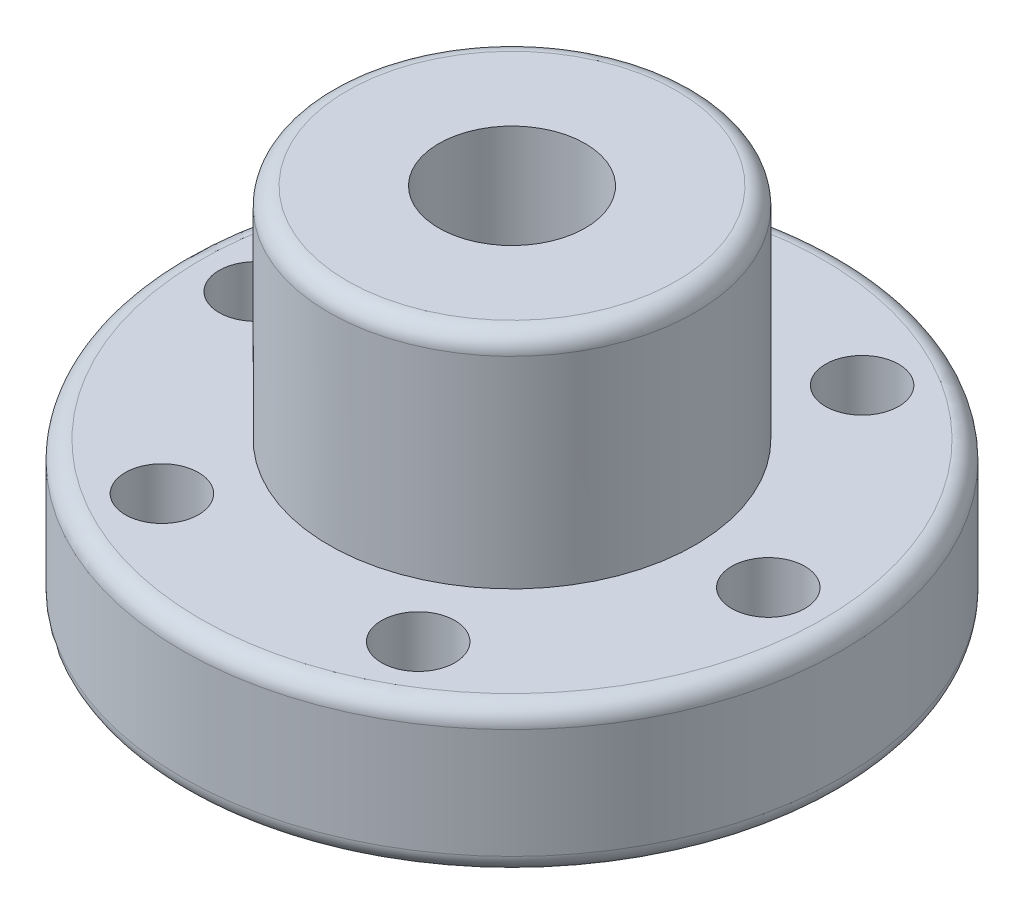
SolidWorks part; units mm, degrees
ref_plane "Front Plane" through (0, 0, 0) normal (0, 0, 1) x (1, 0, 0)
ref_plane "Top Plane" through (0, 0, 0) normal (0, 1, 0) x (1, 0, 0)
ref_plane "Right Plane" through (0, 0, 0) normal (1, 0, 0) x (0, 0, -1)
sketch "Sketch1" plane through (0, 0, 0) normal (0, 0, 1) x (1, 0, 0)
  line L0 (0, 0) -> (0, 20)
  line L1 (0, 20) -> (6, 20)
  line L2 (6, 20) -> (6, 8)
  line L3 (6, 8) -> (14, 8)
  line L4 (14, 8) -> (14, 0)
  line L5 (14, 0) -> (0, 0)
  line L6 (-4, 0) -> (-4, 5.745) construction
  dimension "D1" = 4
  dimension "D2" = 10
  dimension "D3" = 12
  dimension "D4" = 8
  dimension "D5" = 18
revolve "Revolve1" add sketch "Sketch1" angle 360 about L6
fillet "Fillet1" radius 1 3 edges at (-4, 20, -10) (-4, 0, -18) (-4, 8, -18)
sketch "Sketch2" plane through (0, 0, 0) normal (0, -1, 0) x (-1, 0, 0)
  line L0 (18, 0) -> (16, 0) construction
  circle A0 centre (18, 0) radius 2
  circle A1 centre (4, 0) radius 4 construction
  circle A2 centre (11, -12.1244) radius 2
  circle A3 centre (-3, -12.1244) radius 2
  circle A4 centre (-10, 0) radius 2
  circle A5 centre (-3, 12.1244) radius 2
  circle A6 centre (11, 12.1244) radius 2
  point P17 (4, 0)
  dimension "D1" = 4
  dimension "D2" = 14
  dimension "D3" = 6
extrude "Cut-Extrude1" cut sketch "Sketch2" against normal blind 10
